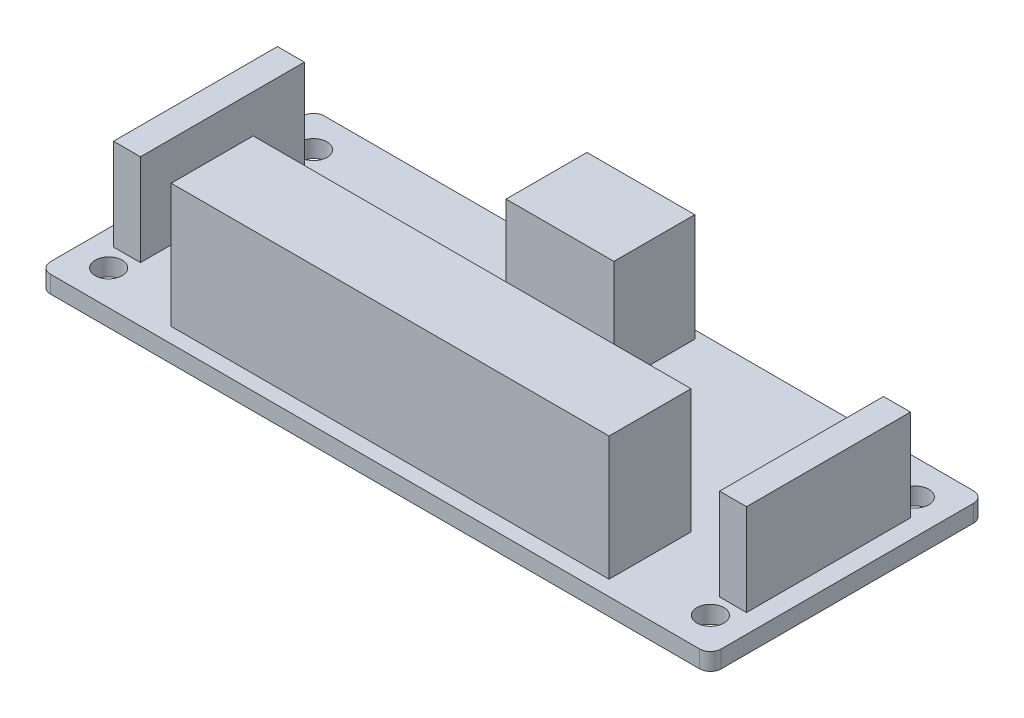
SolidWorks part; units mm, degrees
ref_plane "Front Plane" through (0, 0, 0) normal (0, 0, 1) x (1, 0, 0)
ref_plane "Top Plane" through (0, 0, 0) normal (0, 1, 0) x (1, 0, 0)
ref_plane "Right Plane" through (0, 0, 0) normal (1, 0, 0) x (0, 0, -1)
sketch "Sketch1" plane through (0, 0, 0) normal (0, 1, 0) x (1, 0, 0)
  line L0 (-30.1, 50.7) -> (30.1, 50.7)
  line L1 (31.1, 49.7) -> (31.1, 26.3)
  line L2 (30.1, 25.3) -> (-30.1, 25.3)
  line L3 (-31.1, 26.3) -> (-31.1, 49.7)
  arc A0 (-31.1, 49.7) -> (-30.1, 50.7) centre (-30.1, 49.7) cw
  arc A1 (30.1, 50.7) -> (31.1, 49.7) centre (30.1, 49.7) cw
  arc A2 (31.1, 26.3) -> (30.1, 25.3) centre (30.1, 26.3) cw
  arc A3 (-30.1, 25.3) -> (-31.1, 26.3) centre (-30.1, 26.3) cw
  circle A4 centre (-27.9, 47.5) radius 1.25
  circle A5 centre (-27.9, 28.5) radius 1.25
  circle A6 centre (27.9, 47.5) radius 1.25
  circle A7 centre (27.9, 28.5) radius 1.25
extrude "Board" add sketch "Sketch1" along normal blind 1.6 from offset 8.5
sketch "Sketch2" plane through (0, 0, 0) normal (0, 1, 0) x (1, 0, 0)
  line L0 (-20.3, 34.3) -> (20.3, 34.3)
  line L1 (20.3, 34.3) -> (20.3, 26.7)
  line L2 (20.3, 26.7) -> (-20.3, 26.7)
  line L3 (-20.3, 26.7) -> (-20.3, 34.3)
extrude "Servo headers" add sketch "Sketch2" along normal blind 11.5 from offset 10.1
sketch "Sketch3" plane through (0, 0, 0) normal (0, 1, 0) x (1, 0, 0)
  line L0 (-5, 49.95) -> (5, 49.95)
  line L1 (5, 49.95) -> (5, 42.45)
  line L2 (5, 42.45) -> (-5, 42.45)
  line L3 (-5, 42.45) -> (-5, 49.95)
extrude "V+ terminal" add sketch "Sketch3" along normal blind 10 from offset 10.1
sketch "Sketch4" plane through (0, 0, 0) normal (0, 1, 0) x (1, 0, 0)
  line L0 (-29.35, 45.6) -> (-26.85, 45.6)
  line L1 (-26.85, 45.6) -> (-26.85, 30.4)
  line L2 (-26.85, 30.4) -> (-29.35, 30.4)
  line L3 (-29.35, 30.4) -> (-29.35, 45.6)
  line L4 (26.85, 45.6) -> (29.35, 45.6)
  line L5 (29.35, 45.6) -> (29.35, 30.4)
  line L6 (29.35, 30.4) -> (26.85, 30.4)
  line L7 (26.85, 30.4) -> (26.85, 45.6)
extrude "I2C headers" add sketch "Sketch4" along normal blind 8.5 from offset 10.1
